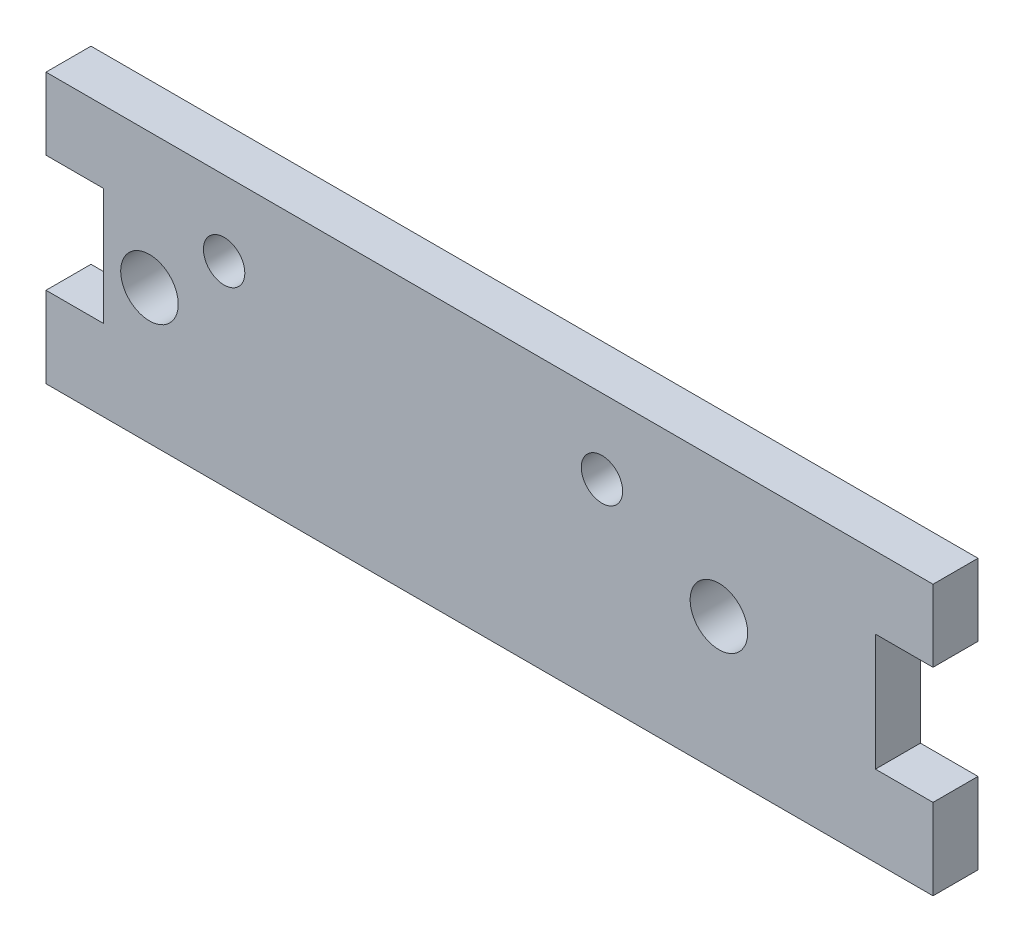
SolidWorks part; units mm, degrees
material "尼龙 101"
ref_plane "前视基准面" through (0, 0, 0) normal (0, 0, 1) x (1, 0, 0)
ref_plane "上视基准面" through (0, 0, 0) normal (0, 1, 0) x (1, 0, 0)
ref_plane "右视基准面" through (0, 0, 0) normal (1, 0, 0) x (0, 0, -1)
other "Configuration Table"
sketch "草图1" plane through (0, 0, 0) normal (0, 0, 1) x (1, 0, 0)
  line L1 (0, 0) -> (49.3, 0)
  line L2 (0, 0) -> (0, 15)
  line L3 (0, 15) -> (49.3, 15)
  line L4 (49.3, 0) -> (49.3, 15)
  dimension "D1" = 49.3
  dimension "D2" = 15
extrude "凸台-拉伸1" add sketch "草图1" along normal blind 2.5
sketch "草图2" plane through (0, 0, 0) normal (0, 0, -1) x (-1, 0, 0)
  line L0 (0, 15) -> (0, 0) construction
  line L1 (-49.3, 15) -> (0, 15) construction
  circle A4 centre (-5.75, 7.5) radius 1.6
  circle A5 centre (-37.4, 7.5) radius 1.6
  dimension "D1" = 3.2
  dimension "D2" = 5.75
  dimension "D4" = 31.65
  dimension "D3" = 7.5
extrude "切除-拉伸1" cut sketch "草图2" against normal through all
sketch "草图3" plane through (0, 0, 2.5) normal (0, 0, 1) x (1, 0, 0)
  line L0 (0, 15) -> (0, 0) construction
  line L1 (0, 11) -> (3.2, 11)
  line L2 (0, 11) -> (0, 4.5)
  line L3 (0, 4.5) -> (3.2, 4.5)
  line L4 (3.2, 11) -> (3.2, 4.5)
  circle A0 centre (5.75, 7.5) radius 1.6 construction
  dimension "D2" = 3.5
  dimension "D1" = 3.2
  dimension "D3" = 6.5
extrude "切除-拉伸2" cut sketch "草图3" against normal blind 10
ref_plane "基准面1" through (24.65, 0, 0) normal (-1, 0, 0) x (0, 0, 1)
mirror "镜向1" about plane through (24.65, 0, 0) normal (-1, 0, 0) of "切除-拉伸2"
sketch "草图4" plane through (0, 0, 2.5) normal (0, 0, 1) x (1, 0, 0)
  circle A0 centre (9.9, 10.85) radius 1.15
  circle A1 centre (30.9, 10.85) radius 1.15
  circle A2 centre (5.75, 7.5) radius 1.6 construction
  dimension "D1" = 3.35
  dimension "D2" = 21
  dimension "D3" = 2.3
  dimension "D4" = 4.15
extrude "切除-拉伸3" cut sketch "草图4" against normal blind 10 contours A0
